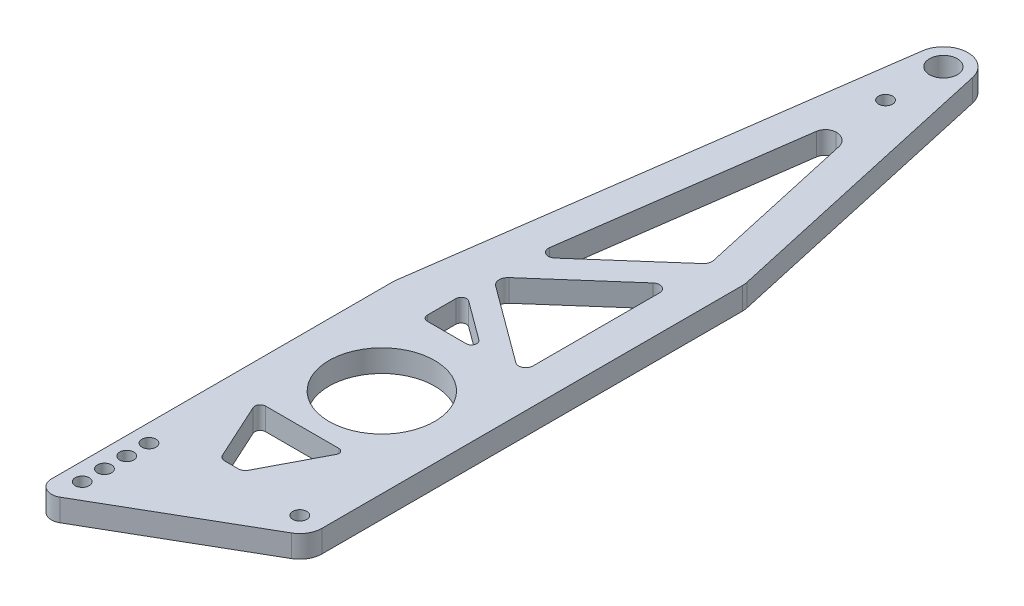
SolidWorks part; units mm, degrees
material "6061-T6 (SS)"
ref_plane "X-Y Datum" through (0, 0, 0) normal (0, 0, 1) x (1, 0, 0)
ref_plane "X-Z Datum" through (0, 0, 0) normal (0, 1, 0) x (1, 0, 0)
ref_plane "Y-Z Datum" through (0, 0, 0) normal (1, 0, 0) x (0, 0, -1)
other "Graphic1" [suppressed]
other "Graphic (Closed) -1" [suppressed]
sketch "Sketch1" plane through (0, 0, 0) normal (0, 1, 0) x (1, 0, 0)
  line L0 (25.4, -82.7357) -> (25.4, -202.7088)
  line L2 (-25.4, -229.1053) -> (-25.4, -131.2787)
  line L6 (25.4, -160.2465) -> (-25.4, -160.2465) construction
  line L28 (22.225, -208.2081) -> (-19.685, -232.4048)
  line L29 (0, 0) -> (41.91, 0) construction
  line L30 (41.91, 0) -> (0, -160.2465) construction
  line L31 (0, -160.2465) -> (0, 0) construction
  line L32 (-20.32, -219.075) -> (-20.32, -212.725) construction
  line L33 (25.2486, -81.3572) -> (6.8184, 1.5163)
  line L34 (-25.4, -131.2787) -> (-6.9178, 0.9668)
  line L35 (4.1417, -31.482) -> (15.3848, -82.0382)
  line L37 (-1.7972, -31.482) -> (-12.2579, -106.3309)
  line L38 (15.3848, -82.0382) -> (-12.2579, -106.3309)
  line L39 (4.1417, -31.482) -> (0, -31.482)
  line L40 (0, -31.482) -> (-1.7972, -31.482)
  line L41 (15.3848, -91.8915) -> (-12.2579, -116.1843)
  line L42 (-12.2579, -116.1843) -> (15.3848, -136.5418)
  line L43 (15.3848, -136.5418) -> (15.3848, -91.8915)
  line L44 (-12.2579, -123.848) -> (4.9785, -136.5418)
  line L45 (4.9785, -136.5418) -> (-12.2579, -136.5418)
  line L46 (-12.2579, -136.5418) -> (-12.2579, -123.848)
  line L47 (-15.24, -180.5665) -> (10.16, -180.5665)
  line L48 (10.16, -180.5665) -> (0, -199.9679)
  line L50 (0, -199.9679) -> (-6.35, -199.9679)
  line L51 (-6.35, -199.9679) -> (-15.24, -180.5665)
  circle A0 centre (0, 0) radius 3.9688
  circle A2 centre (0, -160.2465) radius 15.0813
  circle A6 centre (-20.32, -225.425) radius 2
  circle A7 centre (-20.32, -219.075) radius 2
  circle A8 centre (-20.32, -212.725) radius 2
  circle A9 centre (-20.32, -206.375) radius 2
  arc A10 (6.8184, 1.5163) -> (-6.9178, 0.9668) centre (0, 0) ccw
  circle A41 centre (0, -16.51) radius 2
  arc A42 (-25.4, -229.1053) -> (-19.685, -232.4048) centre (-21.59, -229.1053) ccw
  arc A43 (25.4, -202.7088) -> (22.225, -208.2081) centre (19.05, -202.7088) cw
  circle A44 centre (19.05, -202.7088) radius 2
  circle A45 centre (21.59, -82.0382) radius 2 construction
  arc A46 (25.2486, -81.3572) -> (25.4, -82.7357) centre (19.05, -82.7357) cw
  point P21 (-20.32, -215.9)
  point P30 (25.4, -206.375)
  point P51 (25.4, -82.0382)
  dimension "D1" = 7.9375
  dimension "D4" = 30.1625
  dimension "D8" = 4
  dimension "D6" = 6.985
  dimension "D65" = 4
  dimension "D18" = 3.81
  dimension "D20" = 6.35
  dimension "D22" = 4
  dimension "D32" = 4
  dimension "D34" = 6.35
  dimension "D9" = 5.08
  dimension "D11" = 6.35
  dimension "D12" = 6.35
  dimension "D13" = 6.35
  dimension "D5" = 50.8
  dimension "D66" = 16.51
  dimension "D2" = 41.91
  dimension "D3" = 165.6363
  dimension "D7" = 215.9
  dimension "D10" = 120
  dimension "D19" = 206.375
  dimension "D14" = 9.7764
  dimension "D15" = 9.5626
  dimension "D16" = 7.4014
  dimension "D17" = 6.1709
  dimension "D21" = 10.0152
  dimension "D23" = 187.956
  dimension "D24" = 4.1417
  dimension "D25" = 36.8002
  dimension "D26" = 17.2364
  dimension "D27" = 25.4
  dimension "D28" = 20.32
  dimension "D30" = 10.16
  dimension "D29" = 65.382
  dimension "D31" = 6.35
  dimension "D33" = 3.81
extrude "Boss-Extrude1" add sketch "Sketch1" against normal blind 6.35
sketch "Sketch9" plane through (0, 0, 0) normal (0, 1, 0) x (1, 0, 0)
  line L0 (0, 0) -> (0, -162.7876)
  line L1 (0, -162.7876) -> (41.91, 0)
  line L2 (41.91, 0) -> (0, 0)
  line L3 (0, 0) -> (39.3048, -10.1191) construction
  dimension "D1" = 168.096
  dimension "D2" = 0
  dimension "D3" = 41.91
  dimension "D4" = 40.5865
  dimension "D5" = 75.563
  dimension "D6" = 162.7876
sketch "Sketch4" plane through (0, 0, 0) normal (0, 1, 0) x (1, 0, 0)
  line L0 (0, -34.29) -> (0, 0)
  line L1 (0, 0) -> (152.4, 0)
  line L2 (152.4, 0) -> (0, -34.29)
  line L3 (0, 0) -> (7.3435, -32.6377) construction
  dimension "D1" = 12.68
  dimension "D2" = 156.21
  dimension "D3" = 34.29
  dimension "D4" = 152.4
  dimension "D5" = 33.4537
sketch "Sketch10" plane through (-25.4, 0, 0) normal (-1, 0, 0) x (0, 0, 1)
  line L0 (197.3553, 0) -> (197.3553, -6.35)
  line L1 (131.2787, 0) -> (229.1053, 0) construction
  line L2 (131.2787, -6.35) -> (229.1053, -6.35) construction
  line L5 (229.1053, -6.35) -> (229.1053, 0) construction
  dimension "D1" = 31.75
split line "Split Line1"
fillet "Fillet5" radius 4.064 1 edges at (4.1417, -3.175, 31.482)
fillet "Fillet6" radius 3.048 1 edges at (-1.7972, -3.175, 31.482)
fillet "Fillet7" radius 2.54 1 edges at (15.3848, -3.175, 82.0382)
fillet "Fillet8" radius 2.032 1 edges at (-12.2579, -3.175, 106.3309)
fillet "Fillet9" radius 2.032 1 edges at (15.3848, -3.175, 91.8915)
fillet "Fillet10" radius 2.54 1 edges at (-12.2579, -3.175, 116.1843)
fillet "Fillet11" radius 2.032 1 edges at (15.3848, -3.175, 136.5418)
fillet "Fillet12" radius 1.524 1 edges at (-12.2579, -3.175, 123.848)
fillet "Fillet13" radius 1.524 1 edges at (4.9785, -3.175, 136.5418)
fillet "Fillet14" radius 1.524 1 edges at (-12.2579, -3.175, 136.5418)
fillet "Fillet17" radius 1.27 1 edges at (10.16, -3.175, 180.5665)
fillet "Fillet18" radius 1.524 1 edges at (-15.24, -3.175, 180.5665)
fillet "Fillet19" radius 2.032 1 edges at (-6.35, -3.175, 199.9679)
fillet "Fillet20" radius 2.032 1 edges at (0, -3.175, 199.9679)
equation "\"toePadMount\"=0.25"
equation "\"D11@Sketch1\"=\"toePadMount\""
equation "\"D12@Sketch1\"=\"toePadMount\""
equation "\"D13@Sketch1\"=\"toePadMount\""
